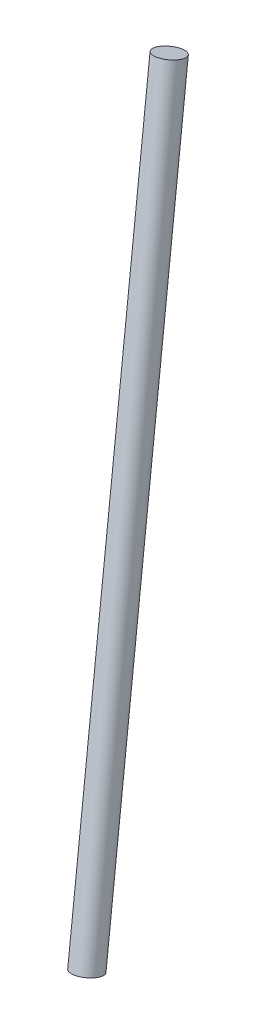
SolidWorks part; units mm, degrees
ref_plane "Front Plane" through (0, 0, 0) normal (0, 0, 1) x (1, 0, 0)
ref_plane "Top Plane" through (0, 0, 0) normal (0, 1, 0) x (1, 0, 0)
ref_plane "Right Plane" through (0, 0, 0) normal (1, 0, 0) x (0, 0, -1)
sketch3d "3DSketch1"
  line L0 (4027.99, 708.66, 306.05) -> (4076.86, 300.53, 404.87) construction
  point P0 (4027.99, 708.66, 306.05)
  point P1 (4076.86, 300.53, 404.87)
sketch3d "3DSketch2"
  line L0 (4029.5569, 695.5745, 309.2184) -> (4074.0295, 324.1684, 399.1465)
  line L1 (4027.99, 708.66, 306.05) -> (4076.86, 300.53, 404.87) construction
sweep "Sweep1" add path "3DSketch2" circular profile diameter 15 parameters "D3"=15
